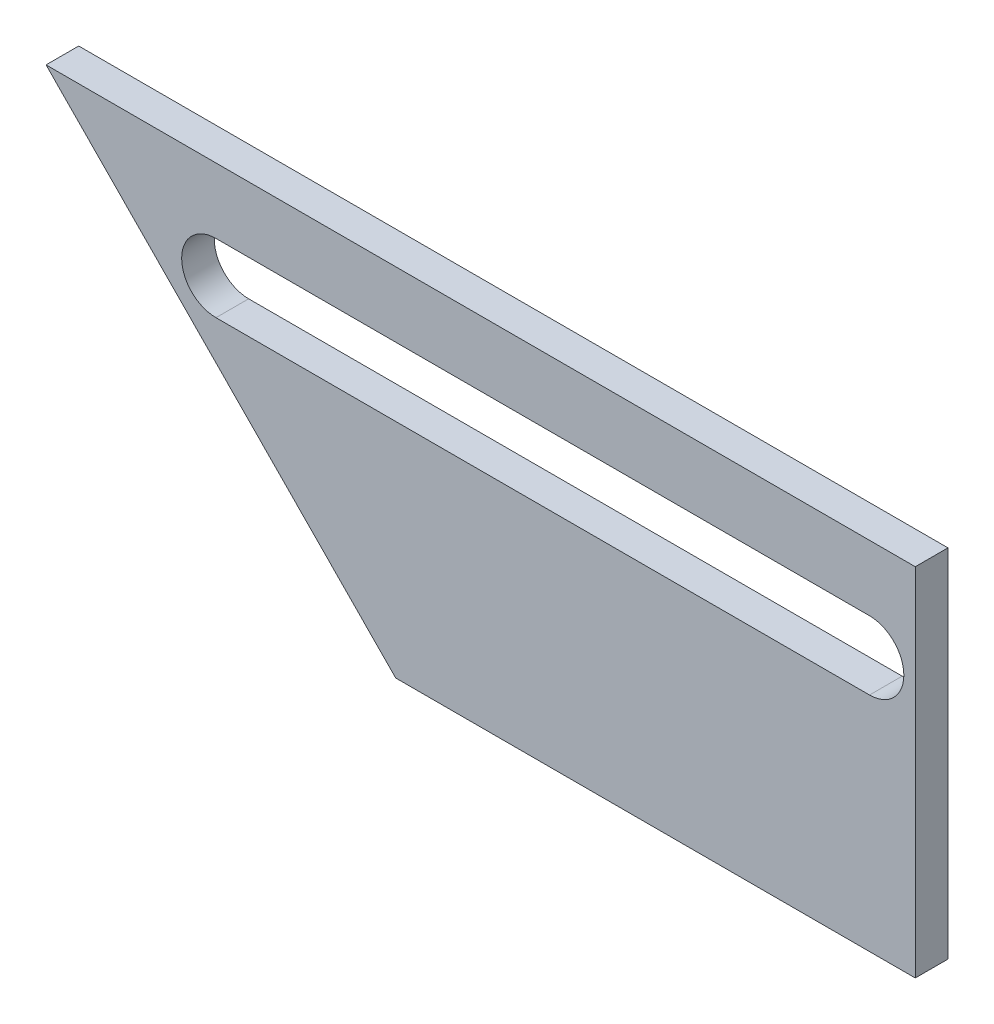
SolidWorks part; units mm, degrees
ref_plane "Front Plane" through (0, 0, 0) normal (0, 0, 1) x (1, 0, 0)
ref_plane "Top Plane" through (0, 0, 0) normal (0, 1, 0) x (1, 0, 0)
ref_plane "Right Plane" through (0, 0, 0) normal (1, 0, 0) x (0, 0, -1)
sketch "Sketch1" plane through (0, 0, 0) normal (0, 0, 1) x (1, 0, 0)
  line L0 (0, 0) -> (0, 54.5)
  line L1 (0, 54.5) -> (-133, 54.5)
  line L2 (-133, 54.5) -> (-79.5, 0)
  line L3 (-79.5, 0) -> (0, 0)
  line L4 (-107, 39.25) -> (-7, 39.25) construction
  line L5 (-107, 44.5) -> (-7, 44.5)
  line L6 (-107, 34) -> (-7, 34)
  arc A0 (-107, 44.5) -> (-107, 34) centre (-107, 39.25) ccw
  arc A1 (-7, 34) -> (-7, 44.5) centre (-7, 39.25) ccw
  point P7 (-57, 39.25)
  dimension "D6" = 100
  dimension "D1" = 133
  dimension "D2" = 54.5
  dimension "D3" = 79.5
  dimension "D4" = 10
  dimension "D5" = 10.5
  dimension "D7" = 7
extrude "Boss-Extrude1" add sketch "Sketch1" along normal blind 5
